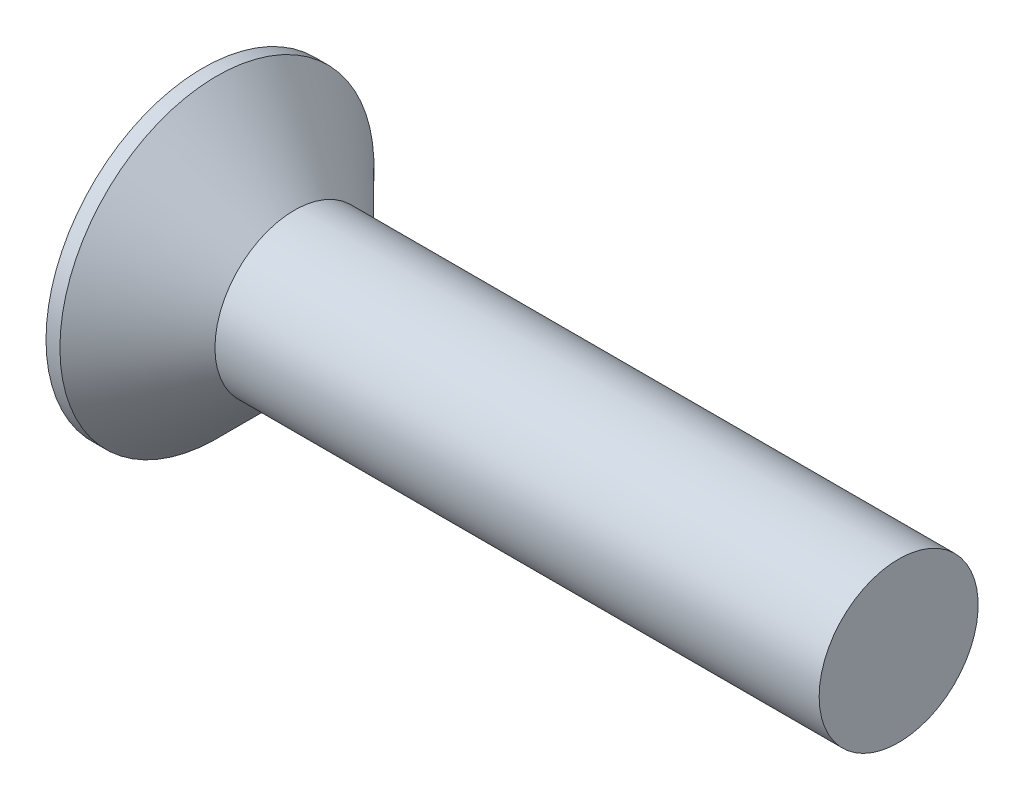
SolidWorks part; units mm, degrees
revolve "Base-Revolve" add sketch "BodySke" angle 360 about L5
sketch "BodySke" plane through (0, 0, 0) normal (0, 0, 1) x (1, 0, 0)
  line L0 (0, 0) -> (0, 7.9)
  line L1 (0, 7.9) -> (0.7, 7.9)
  line L2 (4.6, 4) -> (35, 4)
  line L3 (35, 4) -> (35, 0)
  line L4 (35, 0) -> (0, 0)
  line L5 (-6.35, 0) -> (82.55, 0) construction
  line L6 (4.6, -4) -> (35, -4) construction
  line L7 (0.7, -7.9) -> (4.6, -4) construction
  line L8 (0.7, 7.9) -> (4.6, 4)
  line L9 (0, -7.9) -> (0.7, -7.9) construction
  line L10 (5.85, 5.5875) -> (5.85, -3.9375) construction
  line L11 (0, 6.35) -> (0, -3.175) construction
  dimension "Diameter" = 8
  dimension "Length" = 35
  dimension "Head_ht" = 4.6
  dimension "Head_dia" = 15.8
  dimension "Head_ang" = 90
  dimension "D6" = 0.7
  dimension "Advance" = 1.25
  dimension "Thread_nom" = 35
cosmetic thread "ThreadCosmetic" [suppressed] parameters "Thread_length"=29.15, "Thread_minor"=6.619
extrude "Slot" [suppressed] cut sketch "Sketch2" against normal blind 2.3
sketch "Sketch2" plane through (0, 0, 0) normal (-1, 0, 0) x (0, 0, 1)
  line L0 (-7.9, -1.15) -> (7.9, -1.15)
  line L1 (-7.9, -1.15) -> (-7.9, 1.15)
  line L2 (7.9, 1.15) -> (-7.9, 1.15)
  line L3 (7.9, 1.15) -> (7.9, -1.15)
  dimension "Slot_width" = 2.3
  dimension "D1" = 1.15
  dimension "D2" = 15.8
  dimension "D3" = 7.9
ref_plane "Plane1" through (0, 0, 0) normal (0, 0, 1) x (1, 0, 0)
ref_plane "Plane2" through (0, 0, 0) normal (0, 1, 0) x (1, 0, 0)
ref_plane "Plane3" through (0, 0, 0) normal (1, 0, 0) x (0, 0, -1)
sketch "Sketch3" plane through (0, 0, 0) normal (-1, 0, 0) x (0, 0, 1)
  line L0 (-0.9, 4.39) -> (0.9, 4.39)
  line L1 (0.9, 4.39) -> (0.9, -4.39)
  line L2 (0.9, -4.39) -> (-0.9, -4.39)
  line L3 (-0.9, -4.39) -> (-0.9, 4.39)
  dimension "Cross_dia" = 8.78
  dimension "Cross_width" = 1.8
  dimension "D1" = 4.39
  dimension "D2" = 0.9
ref_plane "Plane4" through (4.88, 0, 0) normal (-1, 0, 0) x (0, 0, 1)
sketch "Sketch4" plane through (4.88, 0, 0) normal (-1, 0, 0) x (0, 0, 1)
  line L0 (-0.45, 0.45) -> (0.45, 0.45)
  line L3 (0.45, 0.45) -> (0.45, -0.45)
  line L4 (0.45, -0.45) -> (-0.45, -0.45)
  line L5 (-0.45, -0.45) -> (-0.45, 0.45)
  dimension "D2" = 0.9
  dimension "D1" = 0.9
  dimension "D3" = 0.45
  dimension "D4" = 0.45
loft "Cross" cut profiles "Sketch3", "Sketch4"
pattern_circular "CirPattern1" count 2 every 90 about axis through (0, 0, 0) along (1, 0, 0) of "Cross"
sketch "ThdSchSke" plane through (0, 0, 0) normal (0, 0, 1) x (1, 0, 0)
  line L0 (5.85, -3.3095) -> (5.3665, -4)
  line L1 (5.85, -3.3095) -> (6.3335, -4)
  line L2 (6.3335, -4) -> (6.3335, -5)
  line L3 (-3.175, 0) -> (5.1513, 0) construction
  line L5 (6.3335, -5) -> (5.3665, -5)
  line L6 (5.3665, -5) -> (5.3665, -4)
  line L7 (0, 7.9) -> (0, -7.9) construction
  dimension "Diameter" = 8
  dimension "Thread_minor" = 6.619
  dimension "Start" = 5.85
revolve "ThreadSchematic" [suppressed] cut sketch "ThdSchSke" angle 360 about L3
pattern_linear "ThdSchPat" [suppressed]
equation "\"D1@Sketch3\" = \"Cross_dia@Sketch3\" / 2"
equation "\"D2@Sketch3\" = \"Cross_width@Sketch3\" / 2"
equation "\"D1@Sketch4\" = \"Cross_width@Sketch3\" *.5"
equation "\"D2@Sketch4\" = \"D1@Sketch4\""
equation "\"D4@Sketch4\" = \"D2@Sketch4\" / 2"
equation "\"D3@Sketch4\" = \"D1@Sketch4\" / 2"
equation "\"D1@Sketch2\" = \"Slot_width@Sketch2\" / 2"
equation "\"D2@Sketch2\" = \"Head_dia@BodySke\""
equation "\"D3@Sketch2\" = \"D2@Sketch2\" / 2"
equation "\"Thread_length@ThreadCosmetic\" = ((sgn( (\"Length@BodySke\" - \"Advance@BodySke\" - \"Head_ht@BodySke\" ) - \"Thread_nom@BodySke\" )-1)*( (\"Length@BodySke\" - \"Advance@BodySke\" - \"Head_ht@BodySke\" ) - \"Thread_nom@BodySke\" ))/-2+ \"Thread_nom@BodySke\""
equation "\"Thread_minor@ThdSchSke\" = \"Thread_minor@ThreadCosmetic\""
equation "\"Diameter@ThdSchSke\" = \"Diameter@BodySke\""
equation "\"Overcut@ThdSchSke\" = \"Diameter@BodySke\" * 1.25"
equation "\"Start@ThdSchSke\" = 0.000001 + \"Length@BodySke\" - \"Thread_length@ThreadCosmetic\"  '---Countersunk---"
equation "\"Num_threads@ThdSchPat\" = int( \"Thread_length@ThreadCosmetic\" / \"Advance@BodySke\" + 0.999 )  + 1"
equation "\"Advance@ThdSchPat\" = \"Thread_length@ThreadCosmetic\" /  (\"Num_threads@ThdSchPat\" - 1) 'relax it"
